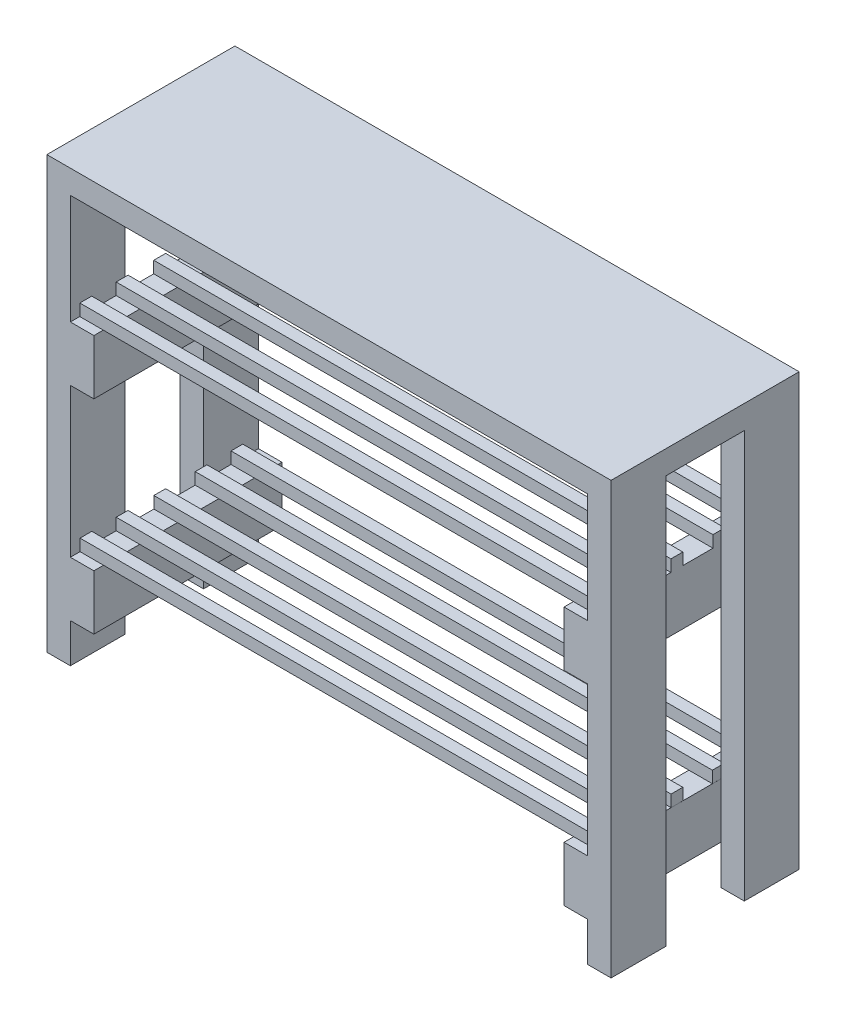
SolidWorks part; units mm, degrees
ref_plane "Front Plane" through (0, 0, 0) normal (0, 0, 1) x (1, 0, 0)
ref_plane "Top Plane" through (0, 0, 0) normal (0, 1, 0) x (1, 0, 0)
ref_plane "Right Plane" through (0, 0, 0) normal (1, 0, 0) x (0, 0, -1)
sketch "Sketch1" plane through (0, 0, 0) normal (0, 1, 0) x (1, 0, 0)
  line L1 (0, 0) -> (914.4, 0)
  line L2 (0, 0) -> (0, 304.8)
  line L3 (0, 304.8) -> (914.4, 304.8)
  line L4 (914.4, 0) -> (914.4, 304.8)
extrude "Boss-Extrude3" add sketch "Sketch1" along normal blind 38.1 contours L3 L4 L1 L2
sketch "Sketch5" plane through (0, 0, 0) normal (0, -1, 0) x (1, 0, 0)
  line L1 (0, 0) -> (38.1, 0)
  line L2 (0, 0) -> (0, -88.9)
  line L3 (0, -88.9) -> (38.1, -88.9)
  line L4 (38.1, 0) -> (38.1, -88.9)
  line L5 (0, -304.8) -> (38.1, -304.8)
  line L6 (0, -304.8) -> (0, -215.9)
  line L7 (0, -215.9) -> (38.1, -215.9)
  line L8 (38.1, -304.8) -> (38.1, -215.9)
  line L9 (914.4, 0) -> (876.3, 0)
  line L10 (914.4, 0) -> (914.4, -88.9)
  line L11 (914.4, -88.9) -> (876.3, -88.9)
  line L12 (876.3, 0) -> (876.3, -88.9)
  line L13 (914.4, -304.8) -> (876.3, -304.8)
  line L14 (914.4, -304.8) -> (914.4, -215.9)
  line L15 (914.4, -215.9) -> (876.3, -215.9)
  line L16 (876.3, -304.8) -> (876.3, -215.9)
extrude "Boss-Extrude4" add sketch "Sketch5" along normal blind 660.4
sketch "Sketch6" plane through (876.3, 0, 0) normal (-1, 0, 0) x (0, 0, 1)
  line L1 (-304.8, 38.1) -> (-304.8, -660.4) construction
  line L2 (-304.8, -177.8) -> (0, -177.8)
  line L3 (-304.8, -177.8) -> (-304.8, -266.7)
  line L4 (-304.8, -266.7) -> (0, -266.7)
  line L5 (0, -177.8) -> (0, -266.7)
  line L6 (0, 38.1) -> (0, -660.4) construction
sketch "Sketch7" plane through (38.1, 0, 0) normal (1, 0, 0) x (0, 0, -1)
  line L1 (304.8, -177.8) -> (0, -177.8)
  line L2 (304.8, -177.8) -> (304.8, -266.7)
  line L3 (304.8, -266.7) -> (0, -266.7)
  line L4 (0, -177.8) -> (0, -266.7)
extrude "Boss-Extrude5" add sketch "Sketch7" along normal blind 38.1
extrude "Boss-Extrude6" add sketch "Sketch6" along normal blind 38.1
sketch "Sketch8" plane through (38.1, 0, 0) normal (1, 0, 0) x (0, 0, -1)
  line L0 (0, 38.1) -> (0, -660.4) construction
  line L1 (0, -596.9) -> (304.8, -596.9)
  line L2 (0, -596.9) -> (0, -508)
  line L3 (0, -508) -> (304.8, -508)
  line L4 (304.8, -596.9) -> (304.8, -508)
  line L5 (304.8, 38.1) -> (304.8, -660.4) construction
sketch "Sketch9" plane through (876.3, 0, 0) normal (-1, 0, 0) x (0, 0, 1)
  line L1 (-304.8, -508) -> (0, -508)
  line L2 (-304.8, -508) -> (-304.8, -596.9)
  line L3 (-304.8, -596.9) -> (0, -596.9)
  line L4 (0, -508) -> (0, -596.9)
extrude "Boss-Extrude7" add sketch "Sketch9" along normal blind 38.1
extrude "Boss-Extrude8" add sketch "Sketch8" along normal blind 38.1 contours L3 L4 L1 L2
sketch "Sketch10" plane through (0, -508, 0) normal (0, 1, 0) x (1, 0, 0)
  line L0 (876.3, 215.9) -> (876.3, 304.8) construction
  line L1 (876.3, 279.4) -> (38.1, 279.4)
  line L2 (876.3, 279.4) -> (876.3, 260.35)
  line L3 (876.3, 260.35) -> (38.1, 260.35)
  line L4 (38.1, 279.4) -> (38.1, 260.35)
  line L5 (38.1, 215.9) -> (38.1, 304.8) construction
  line L6 (876.2674, 221.3809) -> (38.0936, 221.3809)
  line L7 (876.2674, 221.3809) -> (876.2674, 202.3309)
  line L8 (876.2674, 202.3309) -> (38.0936, 202.3309)
  line L9 (38.0936, 221.3809) -> (38.0936, 202.3309)
  line L10 (876.2674, 154.3637) -> (38.1091, 154.3637)
  line L11 (876.2674, 154.3637) -> (876.2674, 135.3137)
  line L12 (876.2674, 135.3137) -> (38.1091, 135.3137)
  line L13 (38.1091, 154.3637) -> (38.1091, 135.3137)
  line L14 (876.2432, 93.3301) -> (38.0675, 93.3301)
  line L15 (876.2432, 93.3301) -> (876.2432, 74.2801)
  line L16 (876.2432, 74.2801) -> (38.0675, 74.2801)
  line L17 (38.0675, 93.3301) -> (38.0675, 74.2801)
  line L18 (876.3, 34.69) -> (38.1261, 34.69)
  line L19 (876.3, 34.69) -> (876.3, 15.64)
  line L20 (876.3, 15.64) -> (38.1261, 15.64)
  line L21 (38.1261, 34.69) -> (38.1261, 15.64)
extrude "Boss-Extrude9" add sketch "Sketch10" along normal blind 19.05
sketch "Sketch11" plane through (0, -177.8, 0) normal (0, 1, 0) x (1, 0, 0)
  line L0 (876.3, 215.9) -> (876.3, 304.8) construction
  line L1 (876.3, 279.4) -> (38.1, 279.4)
  line L2 (876.3, 279.4) -> (876.3, 260.35)
  line L3 (876.3, 260.35) -> (38.1, 260.35)
  line L4 (38.1, 279.4) -> (38.1, 260.35)
  line L5 (38.1, 304.8) -> (38.1, 215.9) construction
  line L6 (38.1, 215.9) -> (38.1, 304.8) construction
  line L7 (38.1, 222.25) -> (876.3, 222.25)
  line L8 (38.1, 222.25) -> (38.1, 203.2)
  line L9 (38.1, 203.2) -> (876.3, 203.2)
  line L10 (876.3, 222.25) -> (876.3, 203.2)
  line L11 (876.3, 215.9) -> (876.3, 88.9) construction
  line L12 (38.1, 88.9) -> (38.1, 215.9) construction
  line L13 (876.3, 154.432) -> (38.1, 154.432)
  line L14 (876.3, 154.432) -> (876.3, 135.128)
  line L15 (876.3, 135.128) -> (38.1, 135.128)
  line L16 (38.1, 154.432) -> (38.1, 135.128)
  line L17 (876.3, 93.4939) -> (38.1, 93.4939)
  line L18 (876.3, 93.4939) -> (876.3, 74.1899)
  line L19 (876.3, 74.1899) -> (38.1, 74.1899)
  line L20 (38.1, 93.4939) -> (38.1, 74.1899)
  line L21 (876.3839, 34.5624) -> (38.1839, 34.5624)
  line L22 (876.3839, 34.5624) -> (876.3839, 15.2584)
  line L23 (876.3839, 15.2584) -> (38.1839, 15.2584)
  line L24 (38.1839, 34.5624) -> (38.1839, 15.2584)
extrude "Boss-Extrude10" add sketch "Sketch11" along normal blind 19.05
